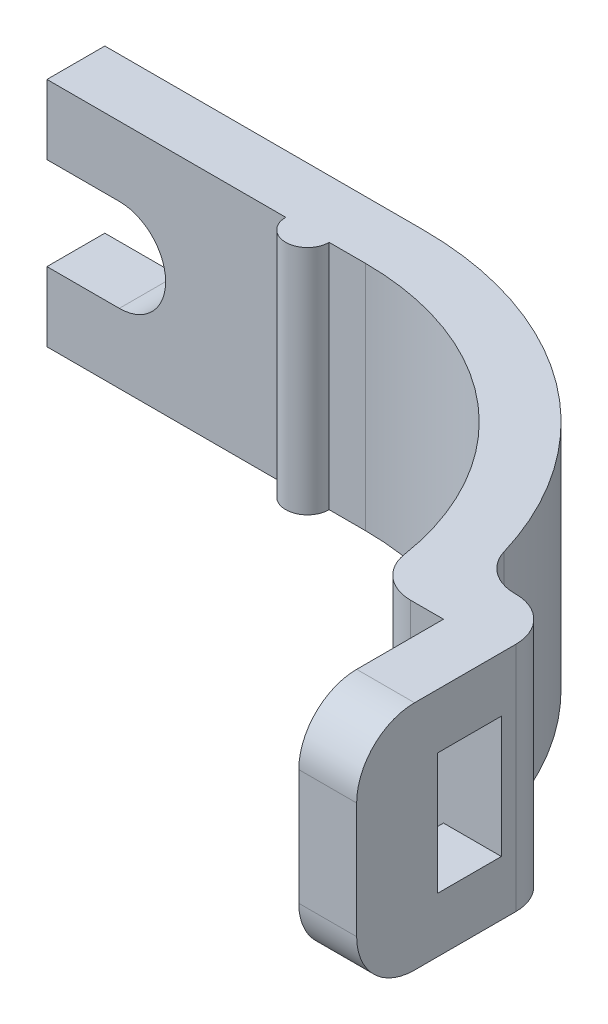
SolidWorks part; units mm, degrees
ref_plane "前视基准面" through (0, 0, 0) normal (0, 0, 1) x (1, 0, 0)
ref_plane "上视基准面" through (0, 0, 0) normal (0, 1, 0) x (1, 0, 0)
ref_plane "右视基准面" through (0, 0, 0) normal (1, 0, 0) x (0, 0, -1)
other "Configuration Table"
sketch "草图1" plane through (0, 0, 0) normal (0, 1, 0) x (1, 0, 0)
  line L0 (9.4979, 0.2) -> (12, 0.2)
  line L1 (12, 0.2) -> (12, -4.8)
  line L2 (0, 9.5) -> (-11, 9.5)
  arc A0 (9.4979, 0.2) -> (0, 9.5) centre (0, 0) ccw
  dimension "D1" = 19
  dimension "D2" = 12
  dimension "D3" = 0.2
  dimension "D4" = 5
  dimension "D5" = 11
extrude "拉伸-薄壁1" add sketch "草图1" along normal blind 8 thin
sketch "草图3" plane through (12, 0, 0) normal (-1, 0, 0) x (0, 0, 1)
  line L0 (-0.2, 8) -> (-0.2, 0) construction
  line L1 (-0.2, 6.1) -> (2, 6.1)
  line L2 (-0.2, 6.1) -> (-0.2, 1.9)
  line L3 (-0.2, 1.9) -> (2, 1.9)
  line L4 (2, 6.1) -> (2, 1.9)
  line L5 (-0.2, 6.1) -> (2, 1.9) construction
  line L6 (-0.2, 1.9) -> (2, 6.1) construction
  line L7 (0.9, 4) -> (4.8, 4) construction
  line L8 (4.8, 8) -> (4.8, 0) construction
  point P4 (0.9, 4)
  dimension "D1" = 4.2
  dimension "D2" = 2.2
extrude "切除-拉伸1" cut sketch "草图3" against normal up to next
sketch "草图4" plane through (0, 0, -11.5) normal (0, 0, -1) x (-1, 0, 0)
  line L0 (11, 4) -> (8.5, 4) construction
  line L1 (11, 8) -> (11, 0) construction
  line L2 (11, 2.4) -> (8.5, 2.4)
  line L3 (11, 5.6) -> (8.5, 5.6)
  line L4 (0, 8) -> (0, 0) construction
  arc A0 (11, 2.4) -> (11, 5.6) centre (11, 4) ccw
  arc A1 (8.5, 5.6) -> (8.5, 2.4) centre (8.5, 4) ccw
  point P4 (9.75, 4)
  dimension "D1" = 1.6
  dimension "D2" = 9.75
extrude "切除-拉伸2" cut sketch "草图4" against normal up to next
fillet "圆角1" radius 1.5 3 edges at (11.2876, 4, -2.2) (9.4979, 4, -0.2) (14, 4, -2.2)
fillet "圆角2" radius 2 2 edges at (13, 8, 4.8) (13, 0, 4.8)
sketch "草图5" plane through (0, 8, 0) normal (0, 1, 0) x (1, 0, 0)
  line L0 (0, 9.5) -> (-11, 9.5) construction
  circle A0 centre (-2, 9.5) radius 0.75
  dimension "D1" = 1.5
  dimension "D2" = 2
extrude "凸台-拉伸1" add sketch "草图5" against normal up to surface (8 mm away) up to face at (6.8452, 0, -3.8464)
